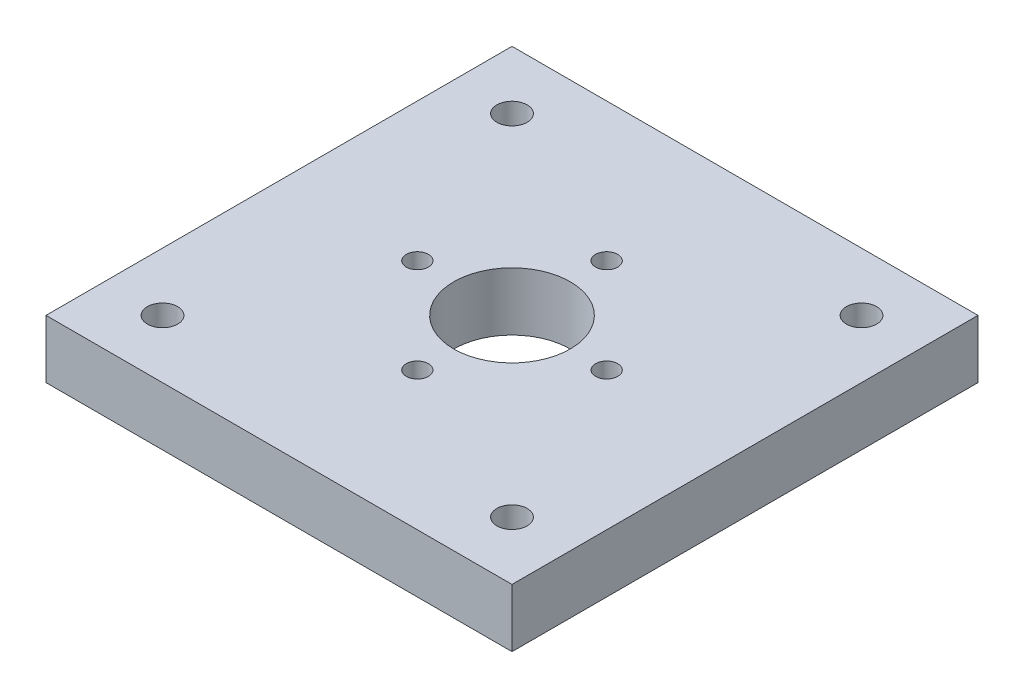
SolidWorks part; units mm, degrees
ref_plane "Front Plane" through (0, 0, 0) normal (0, 0, 1) x (1, 0, 0)
ref_plane "Top Plane" through (0, 0, 0) normal (0, 1, 0) x (1, 0, 0)
ref_plane "Right Plane" through (0, 0, 0) normal (1, 0, 0) x (0, 0, -1)
sketch "Sketch1" plane through (0, 0, 0) normal (0, 1, 0) x (1, 0, 0)
  line L0 (0, 2) -> (0, -2.2901) construction
  line L1 (-2, 2) -> (2, 2)
  line L2 (-2, 2) -> (-2, -2)
  line L3 (-2, -2) -> (2, -2)
  line L4 (2, 2) -> (2, -2)
  line L5 (-2, 2) -> (2, -2) construction
  line L6 (-2, -2) -> (2, 2) construction
  line L7 (-2, 0) -> (2, 0) construction
  circle A0 centre (0, 0) radius 0.5
  circle A1 centre (0, 0) radius 0.8125 construction
  circle A2 centre (1.5, 1.5) radius 0.13
  circle A3 centre (0, 0.8125) radius 0.095
  circle A4 centre (0.8125, 0) radius 0.095
  circle A5 centre (0, -0.8125) radius 0.095
  circle A6 centre (-0.8125, 0) radius 0.095
  circle A7 centre (-1.5, 1.5) radius 0.13
  circle A8 centre (1.5, -1.5) radius 0.13
  circle A9 centre (-1.5, -1.5) radius 0.13
  point P0 (0, 0)
  point P26 (0, 0)
  dimension "D3" = 0.26
  dimension "D4" = 1
  dimension "D5" = 1.625
  dimension "D6" = 0.19
  dimension "D1" = 4
  dimension "D2" = 0.5
  dimension "D7" = 4
extrude "Boss-Extrude1" add sketch "Sketch1" along normal blind 0.5
